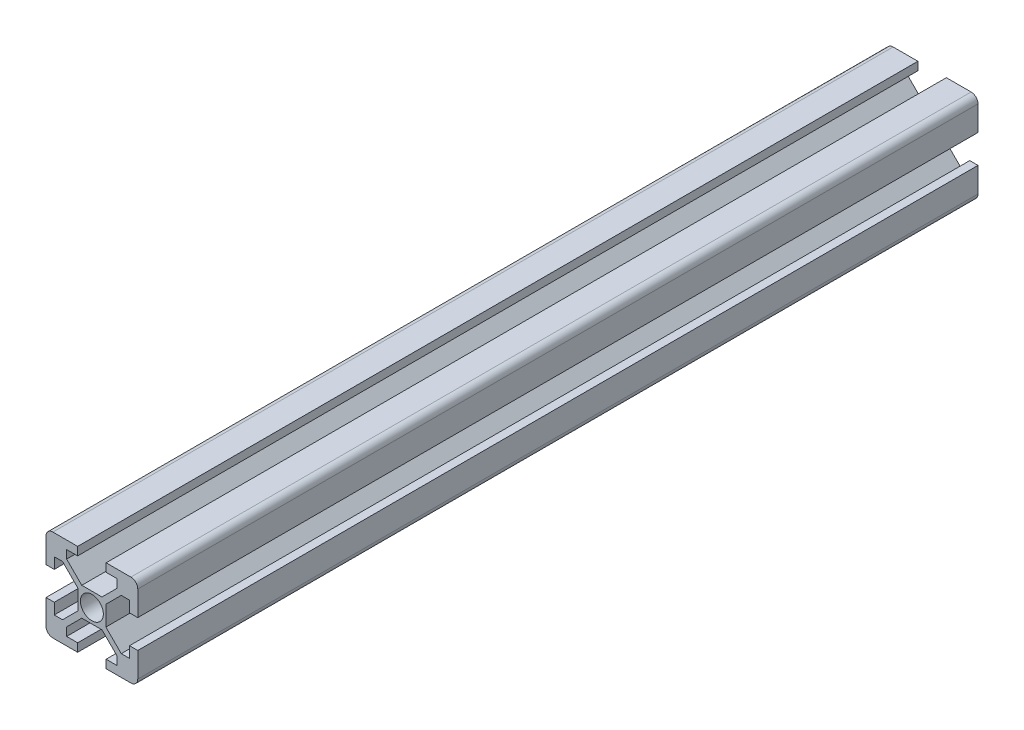
SolidWorks part; units mm, degrees
ref_plane "前视基准面" through (0, 0, 0) normal (0, 0, 1) x (1, 0, 0)
ref_plane "上视基准面" through (0, 0, 0) normal (0, 1, 0) x (1, 0, 0)
ref_plane "右视基准面" through (0, 0, 0) normal (1, 0, 0) x (0, 0, -1)
sketch "草图1" plane through (0, 0, 0) normal (0, 0, 1) x (1, 0, 0)
  line L0 (-10, -3.1) -> (-8.2, -3.1)
  line L1 (-8.5, 10) -> (8.5, 10)
  line L2 (-10, 8.5) -> (-10, -8.5)
  line L3 (-8.5, -10) -> (8.5, -10)
  line L4 (10, 8.5) -> (10, -8.5)
  line L5 (-10, 10) -> (10, -10) construction
  line L6 (-10, -10) -> (10, 10) construction
  line L7 (-3.0541, 3.1) -> (3.0541, 3.1)
  line L8 (-3.0541, 3.1) -> (-3.0541, -3.1)
  line L9 (-3.0541, -3.1) -> (3.0541, -3.1)
  line L10 (3.0541, 3.1) -> (3.0541, -3.1)
  line L11 (-3.0541, 3.1) -> (3.0541, -3.1) construction
  line L12 (-3.0541, -3.1) -> (3.0541, 3.1) construction
  line L13 (-8.2, -3.1) -> (-8.2, -5.5)
  line L14 (-8.2, -5.5) -> (-6.3971, -5.5)
  line L15 (-6.3971, -5.5) -> (-3.0541, -2.1571)
  line L16 (-5.5, 6.3971) -> (-2.1571, 3.0541)
  line L17 (-5.5, 8.2) -> (-5.5, 6.3971)
  line L18 (-3.1, 8.2) -> (-5.5, 8.2)
  line L19 (-3.1, 10) -> (-3.1, 8.2)
  line L20 (6.3971, 5.5) -> (3.0541, 2.1571)
  line L21 (8.2, 5.5) -> (6.3971, 5.5)
  line L22 (8.2, 3.1) -> (8.2, 5.5)
  line L23 (10, 3.1) -> (8.2, 3.1)
  line L24 (5.5, -6.3971) -> (2.1571, -3.0541)
  line L25 (5.5, -8.2) -> (5.5, -6.3971)
  line L26 (3.1, -8.2) -> (5.5, -8.2)
  line L27 (3.1, -10) -> (3.1, -8.2)
  line L28 (-3.1, -10) -> (-3.1, -8.2)
  line L29 (-3.1, -8.2) -> (-5.5, -8.2)
  line L30 (-5.5, -8.2) -> (-5.5, -6.3971)
  line L31 (-5.5, -6.3971) -> (-2.1571, -3.0541)
  line L32 (-8.2, 5.5) -> (-6.3971, 5.5)
  line L33 (-6.3971, 5.5) -> (-3.0541, 2.1571)
  line L34 (-8.2, 3.1) -> (-8.2, 5.5)
  line L35 (-10, 3.1) -> (-8.2, 3.1)
  line L36 (5.5, 8.2) -> (5.5, 6.3971)
  line L37 (5.5, 6.3971) -> (2.1571, 3.0541)
  line L38 (3.1, 8.2) -> (5.5, 8.2)
  line L39 (3.1, 10) -> (3.1, 8.2)
  line L40 (8.2, -5.5) -> (6.3971, -5.5)
  line L41 (6.3971, -5.5) -> (3.0541, -2.1571)
  line L42 (8.2, -3.1) -> (8.2, -5.5)
  line L43 (10, -3.1) -> (8.2, -3.1)
  circle A0 centre (0, 0) radius 2.5
  arc A1 (-10, 8.5) -> (-8.5, 10) centre (-8.5, 8.5) cw
  arc A2 (-10, -8.5) -> (-8.5, -10) centre (-8.5, -8.5) ccw
  arc A3 (8.5, 10) -> (10, 8.5) centre (8.5, 8.5) cw
  arc A4 (10, -8.5) -> (8.5, -10) centre (8.5, -8.5) cw
  point P0 (0, 0)
  point P20 (0, 0)
  point P26 (0, 0)
  point P32 (0, 0)
  point P38 (0, 0)
  point P60 (0, 0)
  dimension "D1" = 4
  dimension "D3" = 1.5
  dimension "D4" = 1.5
  dimension "D5" = 1.5
  dimension "D2" = 4
extrude "凸台-拉伸1" add sketch "草图1" along normal blind 950
sketch "草图2" plane through (0, 0, 950) normal (0, 0, 1) x (1, 0, 0)
  line L1 (82.4853, -16.9043) -> (-27.463, -16.9043)
  line L2 (82.4853, -16.9043) -> (82.4853, 12.5397)
  line L3 (82.4853, 12.5397) -> (-27.463, 12.5397)
  line L4 (-27.463, -16.9043) -> (-27.463, 12.5397)
  line L5 (82.4853, -16.9043) -> (-27.463, 12.5397) construction
  line L6 (82.4853, 12.5397) -> (-27.463, -16.9043) construction
  point P0 (27.5111, -2.1823)
extrude "切除-拉伸1" cut sketch "草图2" against normal blind 725.86
sketch "草图5" plane through (0, 0, 0) normal (0, 0, -1) x (-1, 0, 0)
  line L1 (84.8915, -120.2256) -> (-14.487, -120.2256)
  line L2 (84.8915, -120.2256) -> (84.8915, 31.2339)
  line L3 (84.8915, 31.2339) -> (-14.487, 31.2339)
  line L4 (-14.487, -120.2256) -> (-14.487, 31.2339)
  line L5 (84.8915, -120.2256) -> (-14.487, 31.2339) construction
  line L6 (84.8915, 31.2339) -> (-14.487, -120.2256) construction
  point P0 (35.2022, -44.4958)
extrude "切除-拉伸2" cut sketch "草图5" against normal blind 41
